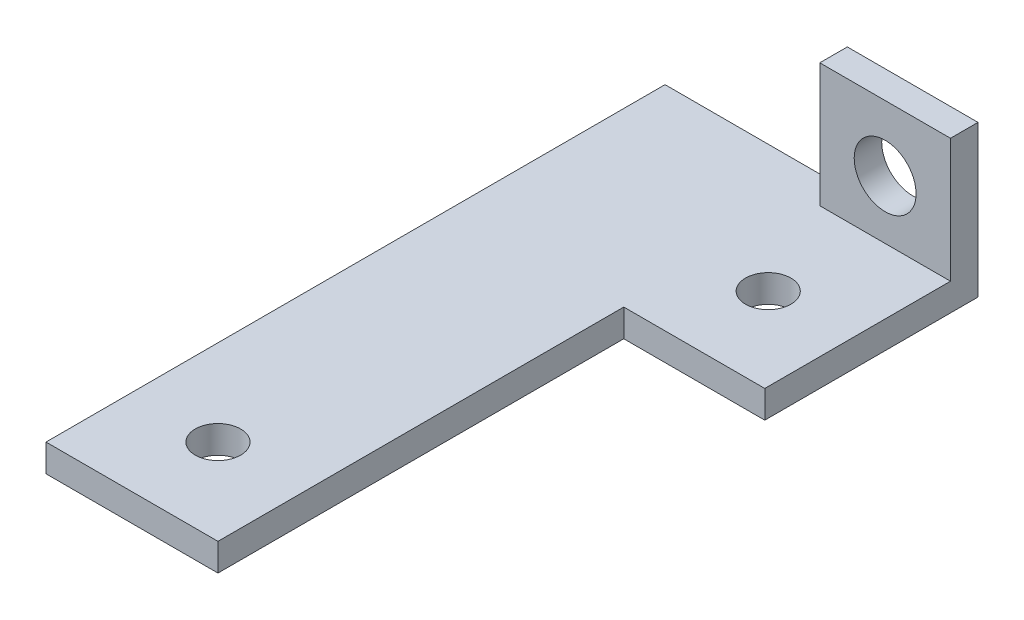
SolidWorks part; units mm, degrees
material "AISI 316 Stainless Steel Sheet (SS)"
ref_plane "Front Plane" through (0, 0, 0) normal (0, 0, 1) x (1, 0, 0)
ref_plane "Top Plane" through (0, 0, 0) normal (0, 1, 0) x (1, 0, 0)
ref_plane "Right Plane" through (0, 0, 0) normal (1, 0, 0) x (0, 0, -1)
sketch "Sketch1" plane through (0, 0, 0) normal (0, 1, 0) x (1, 0, 0)
  line L0 (0, 0) -> (25, 0)
  line L1 (0, 0) -> (0, 90)
  line L4 (0, 90) -> (45.5, 90)
  line L7 (45.5, 90) -> (45.5, 59)
  line L8 (45.5, 59) -> (25, 59)
  line L9 (25, 59) -> (25, 0)
  circle A0 centre (33.5, 71.5) radius 3.3
  circle A1 centre (12.5, 12.5) radius 3.3
  dimension "D7" = 6.6
  dimension "D10" = 6.6
  dimension "D1" = 25
  dimension "D2" = 90
  dimension "D3" = 59
  dimension "D8" = 12
  dimension "D9" = 12.5
  dimension "D11" = 12.5
  dimension "D12" = 12.5
  dimension "D13" = 21
extrude "Boss-Extrude1" add sketch "Sketch1" along normal blind 4
sketch "Sketch2" plane through (0, 4, 0) normal (0, 1, 0) x (1, 0, 0)
  line L0 (45.5, 90) -> (45.5, 86)
  line L1 (45.5, 90) -> (26.5, 90)
  line L2 (45.5, 86) -> (26.5, 86)
  line L3 (26.5, 90) -> (26.5, 86)
  line L5 (45.5, 59) -> (45.5, 90) construction
  line L6 (45.5, 90) -> (0, 90) construction
  dimension "D1" = 19
  dimension "D2" = 4
extrude "Boss-Extrude2" add sketch "Sketch2" along normal blind 18
sketch "Sketch3" plane through (0, 0, -90) normal (0, 0, -1) x (-1, 0, 0)
  line L0 (-26.5, 22) -> (-45.5, 22) construction
  line L2 (-45.5, 22) -> (-45.5, 0) construction
  circle A0 centre (-36, 12.5) radius 4.5
  dimension "D1" = 9
  dimension "D2" = 9.5
  dimension "D3" = 9.5
extrude "Cut-Extrude1" cut sketch "Sketch3" against normal blind 4
